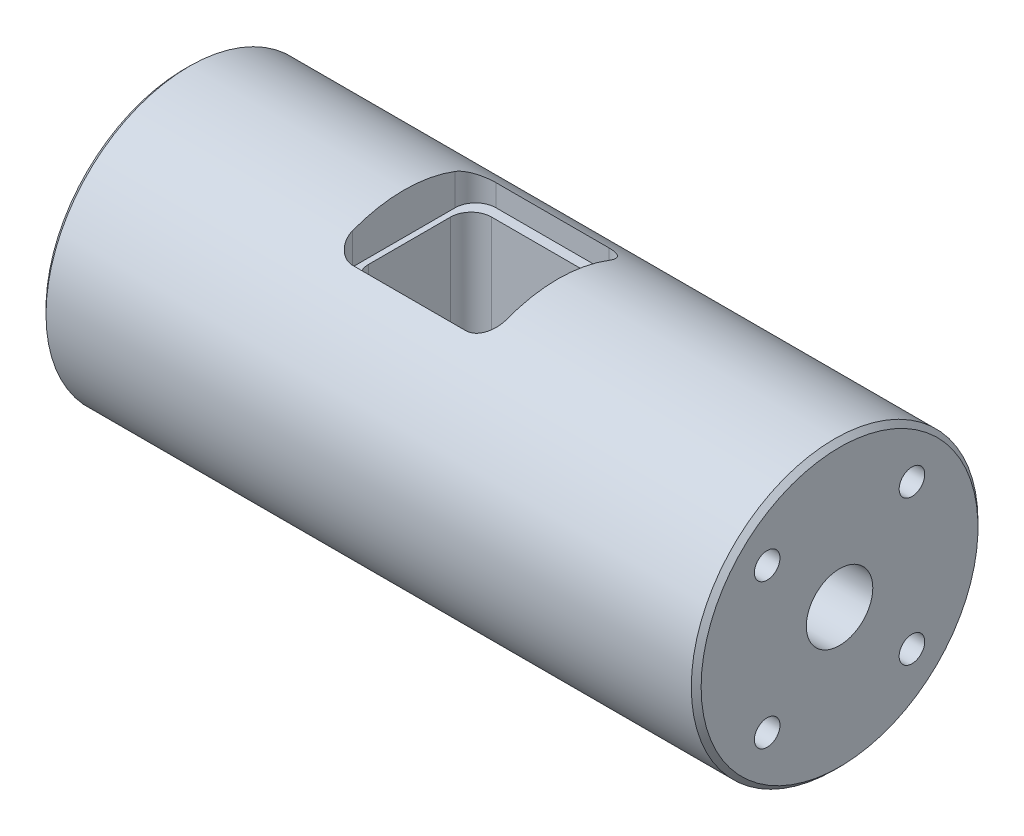
SolidWorks part; units mm, degrees
ref_plane "Front Plane" through (0, 0, 0) normal (0, 0, 1) x (1, 0, 0)
ref_plane "Top Plane" through (0, 0, 0) normal (0, 1, 0) x (1, 0, 0)
ref_plane "Right Plane" through (0, 0, 0) normal (1, 0, 0) x (0, 0, -1)
sketch "Sketch1" plane through (0, 0, 0) normal (0, 1, 0) x (1, 0, 0)
  line L0 (-101.6, 0) -> (-101.6, 44.4627)
  line L1 (-101.6, 44.4627) -> (101.6, 44.4627)
  line L2 (101.6, 44.4627) -> (101.6, 0)
  line L3 (101.6, 0) -> (-101.6, 0)
  line L4 (-127, 0) -> (127, 0) construction
  point P6 (0, 0)
  dimension "D1" = 203.2
  dimension "D2" = 44.4627
revolve "Revolve1" add sketch "Sketch1" angle 360 about L4
chamfer "Chamfer1" distance 1.524 angle 45 2 edges at (101.6, 0, 44.4627) (-101.6, 0, 44.4627)
sketch "Sketch2" plane through (0, 0, 0) normal (0, 1, 0) x (1, 0, 0)
  line L1 (-31.75, -19.05) -> (12.7, -19.05)
  line L2 (-31.75, -19.05) -> (-31.75, 19.05)
  line L3 (-31.75, 19.05) -> (12.7, 19.05)
  line L4 (12.7, -19.05) -> (12.7, 19.05)
  point P8 (0, 0)
  dimension "D1" = 44.45
  dimension "D2" = 38.1
  dimension "D3" = 12.7
  dimension "D4" = 19.05
extrude "Cut-Extrude2" cut sketch "Sketch2" along normal blind 177.8508 from offset 88.9254
fillet "Fillet1" radius 6.35 4 edges at (12.7, 0, -19.05) (-31.75, 0, -19.05) (12.7, 0, 19.05) (-31.75, 0, 19.05)
sketch "Sketch3" plane through (0, 0, 0) normal (0, 1, 0) x (1, 0, 0)
  line L1 (-33.528, -22.225) -> (14.224, -22.225)
  line L2 (-33.528, -22.225) -> (-33.528, 22.225)
  line L3 (-33.528, 22.225) -> (14.224, 22.225)
  line L4 (14.224, -22.225) -> (14.224, 22.225)
  point P8 (0, 0)
  dimension "D1" = 47.752
  dimension "D2" = 44.45
  dimension "D3" = 14.224
  dimension "D4" = 22.225
extrude "Cut-Extrude4" cut sketch "Sketch3" along normal blind 88.9254 from offset 31.7627
fillet "Fillet2" radius 6.35 4 edges at (14.224, 35.1361, -22.225) (-33.528, 35.1361, -22.225) (14.224, 35.1361, 22.225) (-33.528, 35.1361, 22.225)
sketch "Sketch4" plane through (0, 0, 0) normal (1, 0, 0) x (0, 0, -1)
  circle A0 centre (0, 0) radius 18.0578
  point P2 (0, 0)
  dimension "D1" = 36.1156
extrude "Cut-Extrude6" cut sketch "Sketch4" along normal blind 63.5 from offset 101.6
sketch "Sketch5" plane through (0, 0, 0) normal (1, 0, 0) x (0, 0, -1)
  circle A0 centre (0, 0) radius 6.7437
  point P2 (0, 0)
  dimension "D1" = 13.4874
extrude "Cut-Extrude8" cut sketch "Sketch5" against normal blind 95.25 from offset 101.6
sketch "Sketch6" plane through (0, 0, 0) normal (1, 0, 0) x (0, 0, -1)
  circle A0 centre (0, 0) radius 10.3124
  point P2 (0, 0)
  dimension "D1" = 20.6248
extrude "Cut-Extrude10" cut sketch "Sketch6" against normal blind 31.75 from offset 101.6
hole_wizard "3/8-16 Tapped Hole2" positions "Sketch10" profile "Sketch9" tap size "3/8-16" standard "ANSI Inch"
sketch "Sketch10" plane through (101.6, 0, 0) normal (1, 0, 0) x (0, 0, -1)
  line L0 (-22.4536, -22.4536) -> (22.4536, -22.4536) construction
  line L1 (22.4536, -22.4536) -> (22.4536, 22.4536) construction
  line L2 (22.4536, 22.4536) -> (-22.4536, 22.4536) construction
  line L3 (-22.4536, 22.4536) -> (-22.4536, -22.4536) construction
  line L4 (0, 0) -> (22.4536, -22.4536) construction
  circle A0 centre (0, 0) radius 10.3124 construction
  point P0 (-22.4536, -22.4536)
  point P1 (22.4536, -22.4536)
  point P3 (-22.4536, 22.4536)
  point P5 (22.4536, 22.4536)
  dimension "D1" = 22.4536
  dimension "D2" = 22.4536
  dimension "D3" = 22.4536
sketch "Sketch9" plane through (101.6, -22.4536, 22.4536) normal (0, 1, 0) x (0, 0, -1)
  line L0 (0, 0) -> (0, 24.7367)
  line L1 (0, 24.7367) -> (3.9687, 22.352)
  line L2 (3.9687, 22.352) -> (3.9687, 0)
  line L5 (3.9687, 0) -> (0, 0)
  line L10 (0, 24.7367) -> (-3.9687, 22.352) construction
  line L11 (0, -6.35) -> (0, 107.95) construction
  dimension "Tap Drill Dia." = 7.9375
  dimension "Tap Drill Depth" = 22.352
  dimension "Drill Angle" = 118
cosmetic thread "Hole Thread5" parameters "D1"=19.05, "D2"=9.525
cosmetic thread "Hole Thread6" parameters "D1"=19.05, "D2"=9.525
cosmetic thread "Hole Thread7" parameters "D1"=19.05, "D2"=9.525
cosmetic thread "Hole Thread8" parameters "D1"=19.05, "D2"=9.525
